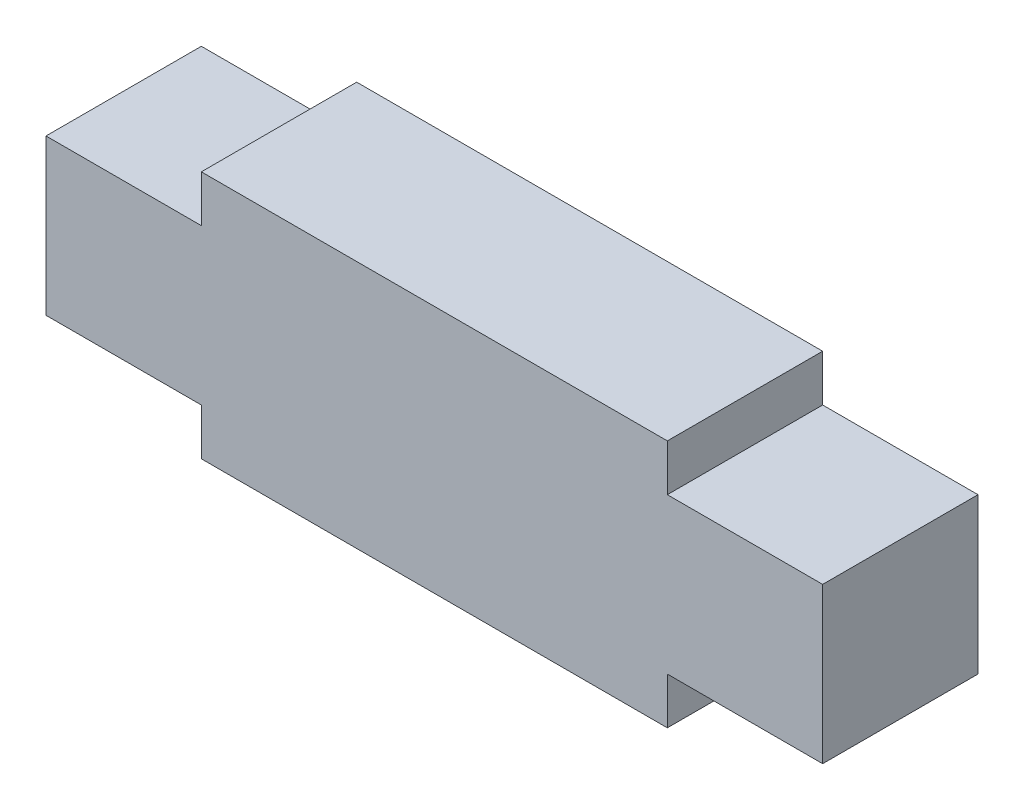
SolidWorks part; units mm, degrees
ref_plane "Front Plane" through (0, 0, 0) normal (0, 0, 1) x (1, 0, 0)
ref_plane "Top Plane" through (0, 0, 0) normal (0, 1, 0) x (1, 0, 0)
ref_plane "Right Plane" through (0, 0, 0) normal (1, 0, 0) x (0, 0, -1)
sketch "Sketch1" plane through (0, 0, 0) normal (0, 0, 1) x (1, 0, 0)
  line L0 (0, 8) -> (0, 6.5)
  line L1 (0, 0) -> (15, 0)
  line L2 (0, 0) -> (0, 8) construction
  line L3 (0, 8) -> (15, 8)
  line L4 (15, 0) -> (15, 8) construction
  line L5 (0, 6.5) -> (-5, 6.5)
  line L6 (-5, 6.5) -> (-5, 1.5)
  line L7 (-5, 1.5) -> (0, 1.5)
  line L8 (0, 1.5) -> (0, 0)
  line L9 (15, 0) -> (15, 1.5)
  line L10 (15, 1.5) -> (20, 1.5)
  line L11 (20, 1.5) -> (20, 6.5)
  line L12 (20, 6.5) -> (15, 6.5)
  line L13 (15, 6.5) -> (15, 8)
  line L14 (15, 4) -> (0, 4) construction
  dimension "D1" = 15
  dimension "D2" = 8
  dimension "D3" = 5
  dimension "D4" = 5
extrude "Boss-Extrude1" add sketch "Sketch1" along normal blind 5
